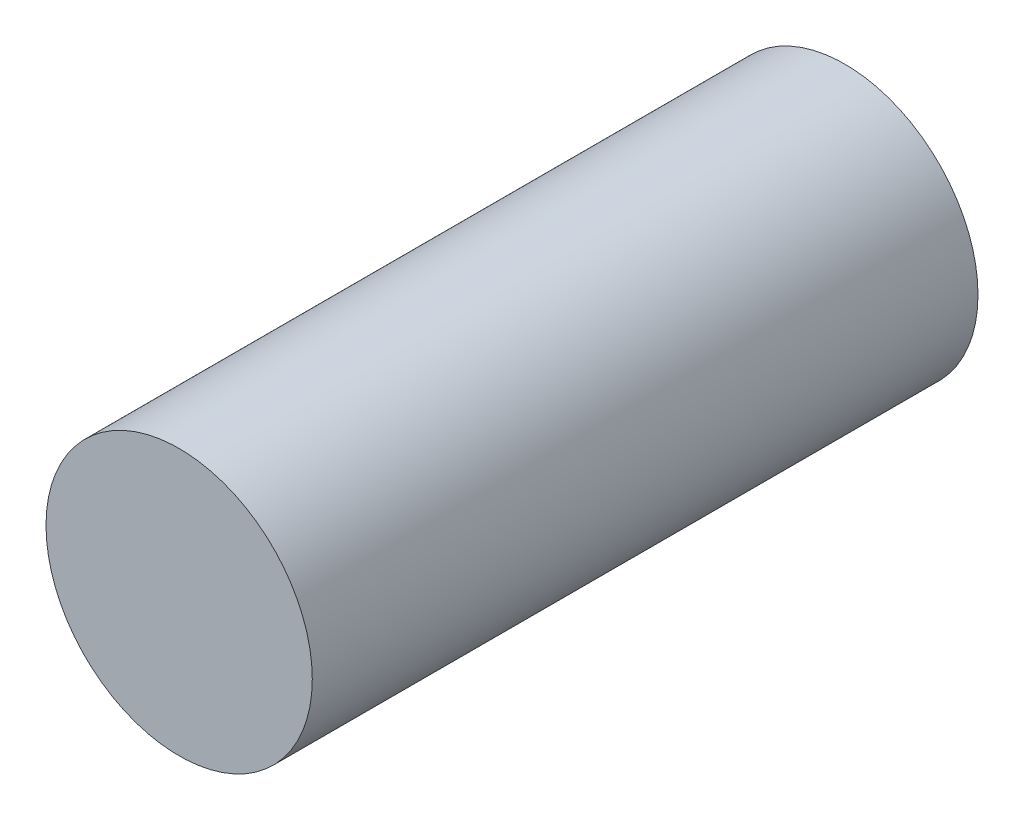
SolidWorks part; units mm, degrees
ref_plane "Front Plane" through (0, 0, 0) normal (0, 0, 1) x (1, 0, 0)
ref_plane "Top Plane" through (0, 0, 0) normal (0, 1, 0) x (1, 0, 0)
ref_plane "Right Plane" through (0, 0, 0) normal (1, 0, 0) x (0, 0, -1)
other "Configuration Table"
sketch "Sketch1" plane through (0, 0, 0) normal (0, 0, 1) x (1, 0, 0)
  circle A0 centre (0, 0) radius 6
extrude "SNS_govde_D12x30" add sketch "Sketch1" against normal blind 30 separate body
